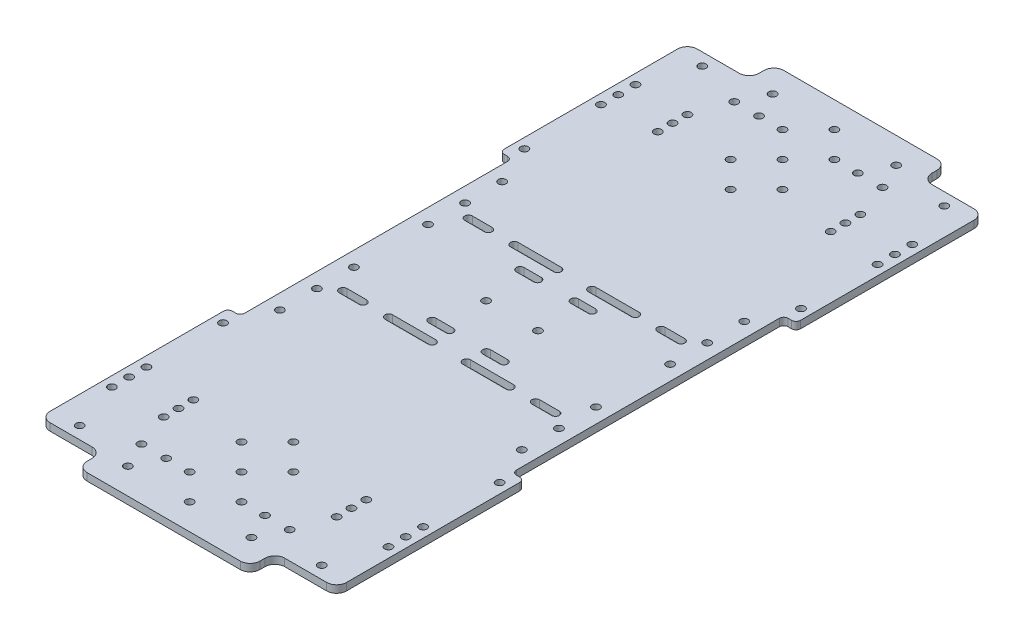
SolidWorks part; units mm, degrees
ref_plane "前视基准面" through (0, 0, 0) normal (0, 0, 1) x (1, 0, 0)
ref_plane "上视基准面" through (0, 0, 0) normal (0, 1, 0) x (1, 0, 0)
ref_plane "右视基准面" through (0, 0, 0) normal (1, 0, 0) x (0, 0, -1)
sketch "草图1" plane through (0, 0, 0) normal (0, 1, 0) x (1, 0, 0)
  line L0 (0, 0) -> (0, -160.6842) construction
  line L5 (0, 0) -> (87.0965, 0) construction
  line L6 (-31, -141) -> (31, -141)
  line L7 (35, -137) -> (35, -135)
  line L8 (39, -131) -> (56, -131)
  line L9 (60, -127) -> (60, -56.8)
  line L10 (58.2, -55) -> (56.8, -55)
  line L11 (55, -53.2) -> (55, 53.2)
  line L12 (10.5, -120) -> (30, -120) construction
  line L13 (-25, -130.5) -> (25, -130.5) construction
  line L14 (35, -106) -> (35, -94) construction
  line L15 (56, -106) -> (56, -92) construction
  line L16 (49, -45) -> (49, -15) construction
  line L17 (7.5, -17.8) -> (14.5, -17.8) construction
  line L18 (7.5, -16.25) -> (14.5, -16.25)
  line L19 (7.5, -19.35) -> (14.5, -19.35)
  line L20 (7, -25.4) -> (24.5, -25.4) construction
  line L21 (7, -23.85) -> (24.5, -23.85)
  line L22 (7, -26.95) -> (24.5, -26.95)
  line L23 (35, -25.4) -> (43, -25.4) construction
  line L24 (35, -23.85) -> (43, -23.85)
  line L25 (35, -26.95) -> (43, -26.95)
  line L26 (56, -92) -> (56, -61) construction
  line L27 (35, -106) -> (56, -106) construction
  line L28 (-35, -106) -> (-56, -106) construction
  line L29 (-56, -92) -> (-56, -61) construction
  line L30 (-49, -45) -> (-49, -15) construction
  line L31 (-56, -106) -> (-56, -92) construction
  line L32 (-35, -106) -> (-35, -94) construction
  line L33 (-10.5, -120) -> (-30, -120) construction
  line L34 (-55, -53.2) -> (-55, 53.2)
  line L35 (-58.2, -55) -> (-56.8, -55)
  line L36 (-60, -127) -> (-60, -56.8)
  line L37 (-39, -131) -> (-56, -131)
  line L38 (-35, -137) -> (-35, -135)
  line L39 (-35, -25.4) -> (-43, -25.4) construction
  line L40 (-35, -23.85) -> (-43, -23.85)
  line L41 (-35, -26.95) -> (-43, -26.95)
  line L42 (-7, -25.4) -> (-24.5, -25.4) construction
  line L43 (-7, -23.85) -> (-24.5, -23.85)
  line L44 (-7, -26.95) -> (-24.5, -26.95)
  line L45 (-7.5, -17.8) -> (-14.5, -17.8) construction
  line L46 (-7.5, -16.25) -> (-14.5, -16.25)
  line L47 (-7.5, -19.35) -> (-14.5, -19.35)
  line L48 (-10.5, 120) -> (-30, 120) construction
  line L49 (-35, 106) -> (-35, 94) construction
  line L50 (-56, 106) -> (-56, 92) construction
  line L51 (-49, 45) -> (-49, 15) construction
  line L52 (-56, 92) -> (-56, 61) construction
  line L53 (-35, 106) -> (-56, 106) construction
  line L54 (35, 106) -> (56, 106) construction
  line L55 (56, 92) -> (56, 61) construction
  line L56 (49, 45) -> (49, 15) construction
  line L57 (56, 106) -> (56, 92) construction
  line L58 (35, 106) -> (35, 94) construction
  line L59 (-25, 130.5) -> (25, 130.5) construction
  line L60 (10.5, 120) -> (30, 120) construction
  line L61 (-35, 137) -> (-35, 135)
  line L62 (-39, 131) -> (-56, 131)
  line L63 (-60, 127) -> (-60, 56.8)
  line L64 (-58.2, 55) -> (-56.8, 55)
  line L65 (58.2, 55) -> (56.8, 55)
  line L66 (60, 127) -> (60, 56.8)
  line L67 (39, 131) -> (56, 131)
  line L68 (35, 137) -> (35, 135)
  line L69 (-31, 141) -> (31, 141)
  line L70 (-7.5, 17.8) -> (-14.5, 17.8) construction
  line L71 (-7.5, 16.25) -> (-14.5, 16.25)
  line L72 (-7.5, 19.35) -> (-14.5, 19.35)
  line L73 (-7, 25.4) -> (-24.5, 25.4) construction
  line L74 (-7, 23.85) -> (-24.5, 23.85)
  line L75 (-7, 26.95) -> (-24.5, 26.95)
  line L76 (-35, 25.4) -> (-43, 25.4) construction
  line L77 (-35, 23.85) -> (-43, 23.85)
  line L78 (-35, 26.95) -> (-43, 26.95)
  line L79 (35, 25.4) -> (43, 25.4) construction
  line L80 (35, 23.85) -> (43, 23.85)
  line L81 (35, 26.95) -> (43, 26.95)
  line L82 (7, 25.4) -> (24.5, 25.4) construction
  line L83 (7, 23.85) -> (24.5, 23.85)
  line L84 (7, 26.95) -> (24.5, 26.95)
  line L85 (7.5, 17.8) -> (14.5, 17.8) construction
  line L86 (7.5, 16.25) -> (14.5, 16.25)
  line L87 (7.5, 19.35) -> (14.5, 19.35)
  circle A0 centre (0, -120) radius 10.5 construction
  circle A1 centre (0, -99) radius 10.5 construction
  circle A2 centre (0, -130.5) radius 1.55
  circle A3 centre (0, -109.5) radius 1.55
  circle A4 centre (0, -88.5) radius 1.55
  circle A5 centre (10.5, -120) radius 1.55
  circle A6 centre (10.5, -99) radius 1.55
  circle A7 centre (20, -120) radius 1.55
  circle A8 centre (30, -120) radius 1.55
  circle A9 centre (25, -130.5) radius 1.55
  circle A10 centre (49, -126) radius 1.55
  circle A11 centre (56, -106) radius 1.55
  circle A12 centre (56, -99) radius 1.55
  circle A13 centre (56, -92) radius 1.55
  circle A14 centre (56, -61) radius 1.55
  circle A15 centre (35, -106) radius 1.55
  circle A16 centre (35, -100) radius 1.55
  circle A17 centre (35, -94) radius 1.55
  circle A18 centre (49, -45) radius 1.55
  circle A19 centre (49, -30) radius 1.55
  circle A20 centre (49, -15) radius 1.55
  circle A21 centre (0, 0) radius 10.5 construction
  circle A22 centre (10.5, 0) radius 1.55
  arc A23 (7.5, -16.25) -> (7.5, -19.35) centre (7.5, -17.8) ccw
  arc A24 (14.5, -19.35) -> (14.5, -16.25) centre (14.5, -17.8) ccw
  arc A25 (7, -23.85) -> (7, -26.95) centre (7, -25.4) ccw
  arc A26 (24.5, -26.95) -> (24.5, -23.85) centre (24.5, -25.4) ccw
  arc A27 (35, -23.85) -> (35, -26.95) centre (35, -25.4) ccw
  arc A28 (43, -26.95) -> (43, -23.85) centre (43, -25.4) ccw
  arc A29 (56, -131) -> (60, -127) centre (56, -127) ccw
  arc A30 (35, -135) -> (39, -131) centre (39, -135) cw
  arc A31 (31, -141) -> (35, -137) centre (31, -137) ccw
  arc A32 (56.8, -55) -> (55, -53.2) centre (56.8, -53.2) cw
  arc A33 (60, -56.8) -> (58.2, -55) centre (58.2, -56.8) ccw
  arc A34 (-60, -56.8) -> (-58.2, -55) centre (-58.2, -56.8) cw
  arc A35 (-56.8, -55) -> (-55, -53.2) centre (-56.8, -53.2) ccw
  arc A36 (-31, -141) -> (-35, -137) centre (-31, -137) cw
  arc A37 (-35, -135) -> (-39, -131) centre (-39, -135) ccw
  arc A38 (-56, -131) -> (-60, -127) centre (-56, -127) cw
  circle A39 centre (-10.5, 0) radius 1.55
  circle A40 centre (-49, -15) radius 1.55
  circle A41 centre (-49, -30) radius 1.55
  circle A42 centre (-49, -45) radius 1.55
  circle A43 centre (-35, -94) radius 1.55
  circle A44 centre (-35, -100) radius 1.55
  circle A45 centre (-35, -106) radius 1.55
  circle A46 centre (-56, -61) radius 1.55
  circle A47 centre (-56, -92) radius 1.55
  circle A48 centre (-56, -99) radius 1.55
  circle A49 centre (-56, -106) radius 1.55
  circle A50 centre (-49, -126) radius 1.55
  circle A51 centre (-25, -130.5) radius 1.55
  circle A52 centre (-30, -120) radius 1.55
  circle A53 centre (-20, -120) radius 1.55
  circle A54 centre (-10.5, -99) radius 1.55
  circle A55 centre (-10.5, -120) radius 1.55
  arc A56 (-35, -23.85) -> (-35, -26.95) centre (-35, -25.4) cw
  arc A57 (-43, -26.95) -> (-43, -23.85) centre (-43, -25.4) cw
  arc A58 (-7, -23.85) -> (-7, -26.95) centre (-7, -25.4) cw
  arc A59 (-24.5, -26.95) -> (-24.5, -23.85) centre (-24.5, -25.4) cw
  arc A60 (-7.5, -16.25) -> (-7.5, -19.35) centre (-7.5, -17.8) cw
  arc A61 (-14.5, -19.35) -> (-14.5, -16.25) centre (-14.5, -17.8) cw
  circle A62 centre (0, 99) radius 10.5 construction
  circle A63 centre (0, 120) radius 10.5 construction
  circle A64 centre (-10.5, 120) radius 1.55
  circle A65 centre (-10.5, 99) radius 1.55
  circle A66 centre (-20, 120) radius 1.55
  circle A67 centre (-30, 120) radius 1.55
  circle A68 centre (-25, 130.5) radius 1.55
  circle A69 centre (-49, 126) radius 1.55
  circle A70 centre (-56, 106) radius 1.55
  circle A71 centre (-56, 99) radius 1.55
  circle A72 centre (-56, 92) radius 1.55
  circle A73 centre (-56, 61) radius 1.55
  circle A74 centre (-35, 106) radius 1.55
  circle A75 centre (-35, 100) radius 1.55
  circle A76 centre (-35, 94) radius 1.55
  circle A77 centre (-49, 45) radius 1.55
  circle A78 centre (-49, 30) radius 1.55
  circle A79 centre (-49, 15) radius 1.55
  arc A80 (-56, 131) -> (-60, 127) centre (-56, 127) ccw
  arc A81 (-35, 135) -> (-39, 131) centre (-39, 135) cw
  arc A82 (-31, 141) -> (-35, 137) centre (-31, 137) ccw
  arc A83 (-56.8, 55) -> (-55, 53.2) centre (-56.8, 53.2) cw
  arc A84 (-60, 56.8) -> (-58.2, 55) centre (-58.2, 56.8) ccw
  arc A85 (60, 56.8) -> (58.2, 55) centre (58.2, 56.8) cw
  arc A86 (56.8, 55) -> (55, 53.2) centre (56.8, 53.2) ccw
  arc A87 (31, 141) -> (35, 137) centre (31, 137) cw
  arc A88 (35, 135) -> (39, 131) centre (39, 135) ccw
  arc A89 (56, 131) -> (60, 127) centre (56, 127) cw
  circle A90 centre (49, 15) radius 1.55
  circle A91 centre (49, 30) radius 1.55
  circle A92 centre (49, 45) radius 1.55
  circle A93 centre (35, 94) radius 1.55
  circle A94 centre (35, 100) radius 1.55
  circle A95 centre (35, 106) radius 1.55
  circle A96 centre (56, 61) radius 1.55
  circle A97 centre (56, 92) radius 1.55
  circle A98 centre (56, 99) radius 1.55
  circle A99 centre (56, 106) radius 1.55
  circle A100 centre (49, 126) radius 1.55
  circle A101 centre (25, 130.5) radius 1.55
  circle A102 centre (30, 120) radius 1.55
  circle A103 centre (20, 120) radius 1.55
  circle A104 centre (10.5, 99) radius 1.55
  circle A105 centre (10.5, 120) radius 1.55
  circle A106 centre (0, 88.5) radius 1.55
  circle A107 centre (0, 109.5) radius 1.55
  circle A108 centre (0, 130.5) radius 1.55
  arc A109 (-7.5, 16.25) -> (-7.5, 19.35) centre (-7.5, 17.8) ccw
  arc A110 (-14.5, 19.35) -> (-14.5, 16.25) centre (-14.5, 17.8) ccw
  arc A111 (-7, 23.85) -> (-7, 26.95) centre (-7, 25.4) ccw
  arc A112 (-24.5, 26.95) -> (-24.5, 23.85) centre (-24.5, 25.4) ccw
  arc A113 (-35, 23.85) -> (-35, 26.95) centre (-35, 25.4) ccw
  arc A114 (-43, 26.95) -> (-43, 23.85) centre (-43, 25.4) ccw
  arc A115 (35, 23.85) -> (35, 26.95) centre (35, 25.4) cw
  arc A116 (43, 26.95) -> (43, 23.85) centre (43, 25.4) cw
  arc A117 (7, 23.85) -> (7, 26.95) centre (7, 25.4) cw
  arc A118 (24.5, 26.95) -> (24.5, 23.85) centre (24.5, 25.4) cw
  arc A119 (7.5, 16.25) -> (7.5, 19.35) centre (7.5, 17.8) cw
  arc A120 (14.5, 19.35) -> (14.5, 16.25) centre (14.5, 17.8) cw
  point P2 (-35, -131)
  point P59 (11, -17.8)
  point P64 (15.75, -25.4)
  point P71 (39, -25.4)
  point P79 (60, -131)
  point P82 (35, -131)
  point P138 (55, 0)
  point P139 (0, -141)
  point P140 (-60, -131)
  point P143 (-39, -25.4)
  point P150 (-15.75, -25.4)
  point P157 (-11, -17.8)
  point P266 (-55, 0)
  point P268 (-11, 17.8)
  point P275 (-15.75, 25.4)
  point P282 (-39, 25.4)
  point P287 (-60, 131)
  point P288 (0, 141)
  point P289 (35, 131)
  point P290 (60, 131)
  point P293 (39, 25.4)
  point P300 (15.75, 25.4)
  point P307 (11, 17.8)
  point P312 (-35, 131)
  dimension "D5" = 21
  dimension "D9" = 3.1
  dimension "D16" = 21
  dimension "D23" = 1.55
  dimension "D24" = 1.55
  dimension "D25" = 1.55
  dimension "D39" = 4
  dimension "D40" = 1.8
  dimension "D1" = 282
  dimension "D2" = 120
  dimension "D3" = 110
  dimension "D4" = 110
  dimension "D6" = 240
  dimension "D7" = 198
  dimension "D8" = 21
  dimension "D10" = 50
  dimension "D11" = 60
  dimension "D12" = 40
  dimension "D13" = 90
  dimension "D14" = 30
  dimension "D15" = 60
  dimension "D17" = 15
  dimension "D18" = 29
  dimension "D19" = 14
  dimension "D20" = 49
  dimension "D21" = 70
  dimension "D22" = 86
  dimension "D26" = 17.8
  dimension "D27" = 25.4
  dimension "D28" = 49
  dimension "D29" = 262
  dimension "D30" = 25
  dimension "D31" = 14
  dimension "D32" = 56
  dimension "D33" = 31
  dimension "D34" = 122
  dimension "D35" = 252
  dimension "D36" = 12
  dimension "D37" = 49
  dimension "D38" = 0
extrude "凸台-拉伸1" add sketch "草图1" along normal blind 3
